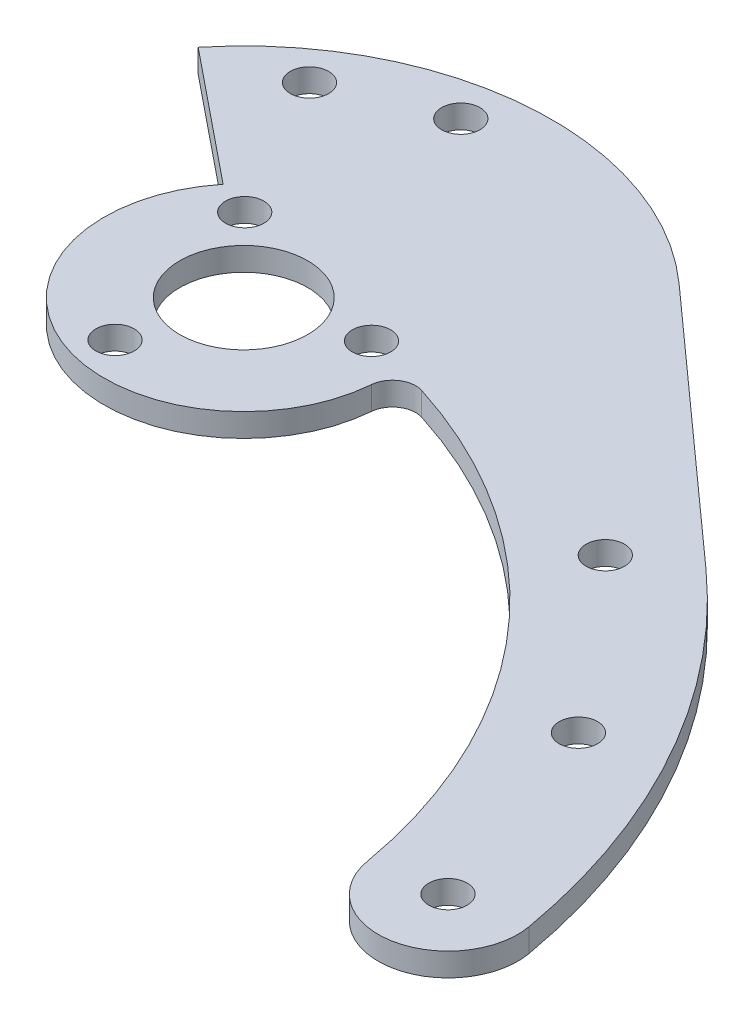
SolidWorks part; units mm, degrees
ref_plane "Спереди" through (0, 0, 0) normal (0, 0, 1) x (1, 0, 0)
ref_plane "Сверху" through (0, 0, 0) normal (0, 1, 0) x (1, 0, 0)
ref_plane "Справа" through (0, 0, 0) normal (1, 0, 0) x (0, 0, -1)
sketch "Эскиз1" plane through (0, 0, 0) normal (0, 1, 0) x (1, 0, 0)
  line L0 (0, 0) -> (-28.7056, 23.2454) construction
  line L1 (0, -44.9991) -> (75.8377, -31.6268) construction
  line L2 (-19.6703, 19.9268) -> (51.7327, -52.4073) construction
  line L3 (0, 0) -> (-9.6836, 9.8099) construction
  line L4 (0, -44.9991) -> (0, 0) construction
  line L5 (0, 0) -> (13.3374, 3.4813) construction
  line L6 (0, 0) -> (-4.7339, -17.2201) construction
  line L7 (0, -44.9991) -> (77.7218, -44.9991) construction
  line L8 (40.06, -0.3315) -> (32.048, -9.265) construction
  line L9 (-9.3258, 7.5518) -> (-20.5944, 16.677)
  line L10 (40.06, -0.3315) -> (17.6932, 19.7282)
  line L11 (0, 26.5) -> (0, 0) construction
  arc A0 (0, 26.5) -> (-20.5944, 16.677) centre (0, 0) ccw
  arc A1 (0, 26.5) -> (17.6932, 19.7282) centre (0, 0) cw
  circle A2 centre (0, 0) radius 9 construction
  circle A3 centre (0, 0) radius 10.65 construction
  circle A4 centre (-6.3226, 6.4051) radius 1.65
  circle A5 centre (0, 0) radius 5.5
  circle A6 centre (8.7082, 2.273) radius 1.65
  circle A7 centre (-2.3856, -8.6781) radius 1.65
  arc A8 (-9.3258, 7.5518) -> (11.9058, 1.501) centre (0, 0) ccw
  circle A10 centre (0, -44.9991) radius 48 construction
  arc A11 (47.2708, -36.6639) -> (11.9058, 1.501) centre (0, -44.9991) ccw
  arc A12 (40.06, -0.3315) -> (59.0885, -34.5802) centre (0, -44.9991) cw
  circle A13 centre (0, -44.9991) radius 54 construction
  arc A14 (59.0885, -34.5802) -> (47.2708, -36.6639) centre (53.1796, -35.6221) cw
  point P12 (36.054, -4.7982)
  dimension "D1" = 26.5
  dimension "D2" = 48
  dimension "D6" = 18
  dimension "D7" = 12
  dimension "D9" = 120
  dimension "D4" = 11
  dimension "D8" = 21.3
  dimension "D5" = 44.9991
  dimension "D11" = 60
  dimension "D12" = 80
  dimension "D13" = 51
  dimension "D3" = 90
  dimension "D10" = 120
extrude "Бобышка-Вытянуть1" add sketch "Эскиз1" along normal blind 2
sketch "Эскиз2" plane through (0, 2, 0) normal (0, 1, 0) x (1, 0, 0)
  line L0 (0, 0) -> (0, 16.5609) construction
  line L1 (0, 0) -> (-2.989, 16.9517) construction
  line L2 (0, 0) -> (-6.9675, 16.8209) construction
  line L3 (0, -45) -> (34.7105, -3.6336) construction
  line L4 (0, -45) -> (46.7654, -18) construction
  line L5 (0, -45) -> (53.1796, -35.623) construction
  line L7 (0, 0) -> (0, -45) construction
  circle A0 centre (0, 0) radius 23 construction
  circle A1 centre (-3.9939, 22.6506) radius 1.65
  circle A2 centre (-13.1923, 18.8405) radius 1.65
  circle A3 centre (46.7654, -18) radius 1.65
  circle A4 centre (53.1796, -35.623) radius 1.65
  circle A5 centre (34.7105, -3.6336) radius 1.65
  circle A6 centre (0, -45) radius 54 construction
  dimension "D2" = 22.5
  dimension "D3" = 46
  dimension "D4" = 3.3
  dimension "D7" = 40
  dimension "D9" = 80
  dimension "D10" = 3.3
  dimension "D11" = 3.3
  dimension "D12" = 3.3
  dimension "D5" = 45
  dimension "D6" = 108
  dimension "D1" = 10
  dimension "D8" = 60
extrude "Вырез-Вытянуть2" cut sketch "Эскиз2" against normal through all
fillet "Скругление1" radius 2 1 edges at (11.9058, 1, -1.501)
